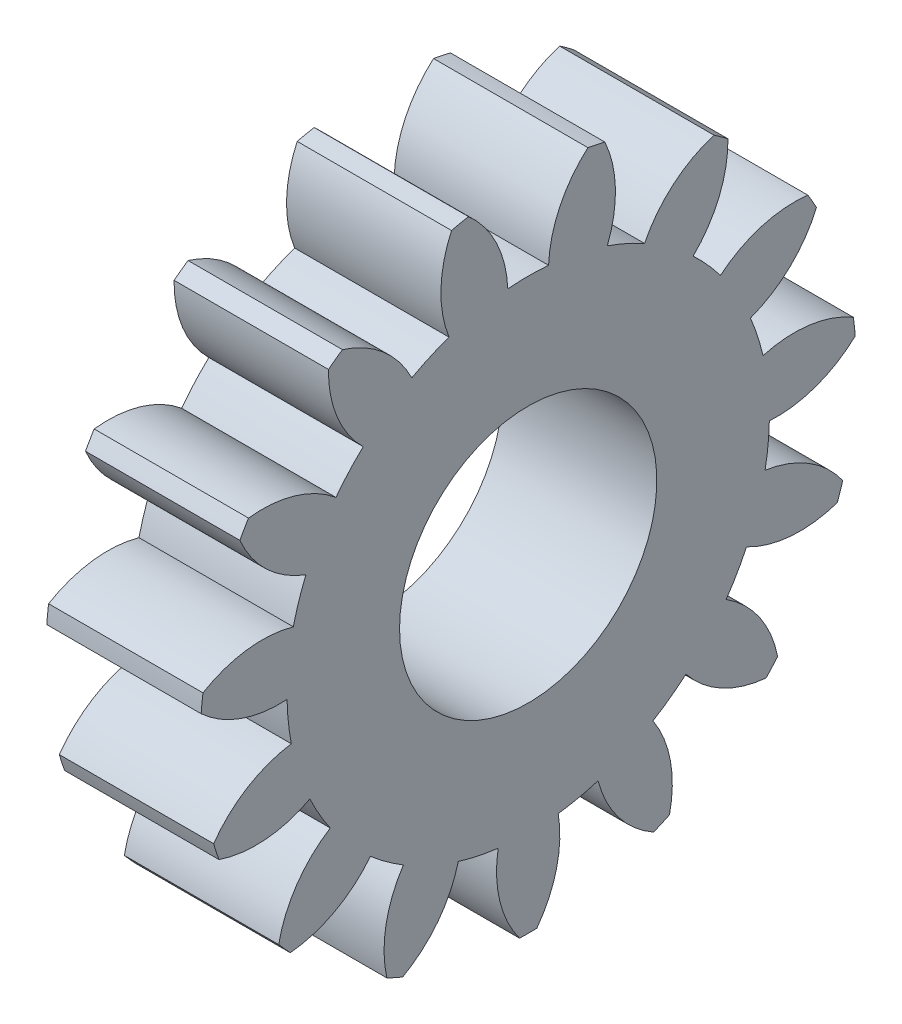
SolidWorks part; units mm, degrees
ref_plane "Plane1" through (0, 0, 0) normal (0, 0, 1) x (1, 0, 0)
ref_plane "Plane2" through (0, 0, 0) normal (0, 1, 0) x (1, 0, 0)
ref_plane "Plane3" through (0, 0, 0) normal (1, 0, 0) x (0, 0, -1)
other "Configuration Table"
sketch "HoldingSke" plane through (0, 0, 0) normal (0, 1, 0) x (1, 0, 0)
  line L0 (0, 0) -> (0.322, -0.0863)
  line L1 (-15, 0) -> (100, 0) construction
  line L2 (0, 0) -> (-2.1039, 2.3779)
  line L3 (0, 0) -> (-11.863, 4.5341)
  line L4 (0, 0) -> (8.3417, 2.2352)
  line L5 (0, 0) -> (-46.8476, -17.4728)
  line L6 (0, 0) -> (-9.9476, -6.7116)
  line L7 (-2.1039, 2.3779) -> (8.6586, 51.2059)
  line L8 (-76.2, 54.61) -> (-73.4, 54.61)
  line L9 (-71.009, 38.7566) -> (-53.1078, 45.2721)
  line L10 (-76.2, 71.12) -> (104.1128, 71.12)
  line L11 (0, 0) -> (-12, 0)
  line L12 (-76.2, 101.6) -> (-76.093, 101.6)
  line L13 (24.9733, 27.94) -> (52.9518, 28.4284)
  line L14 (24.9733, 27.94) -> (24.9743, 27.94)
  line L15 (24.9733, 27.94) -> (100.4006, 29.5858)
  line L16 (-63.627, -3) -> (-12.827, -3)
  circle A0 centre (0, 0) radius 10
  circle A1 centre (0, 0) radius 18.749
  circle A2 centre (0, 0) radius 37.5
  circle A3 centre (0, 0) radius 10
  dimension "MHD" = 37.498
  dimension "Hub_dia" = 75
  dimension "Bore" = 20
  dimension "MBD" = 20
  dimension "Num_teeth" = 15
  dimension "Pitch" = 0.3333
  dimension "Overall_len" = 50
  dimension "Show_teeth" = 15
  dimension "Thickness" = 12
  dimension "OAL" = 50.0001
  dimension "T_dim" = 2.8
  dimension "Ap" = 20
  dimension "H" = 19.05
  dimension "Pitch_radius" = 180.3128
  dimension "Width" = 12
  dimension "Backlash" = 0.107
  dimension "Addendum_fac" = 1
  dimension "Dedendum_fac" = 1.25
  dimension "Clearance_fac" = 0.25
  dimension "Dedendum_add" = 0.001
  dimension "Module" = 3
sketch "BasProSke" plane through (0, 0, 0) normal (0, 1, 0) x (1, 0, 0)
  line L0 (-10, 0) -> (60, 0) construction
  line L1 (0, 0) -> (0, 25.5)
  line L2 (0, 0) -> (12, 0)
  line L3 (12, 0) -> (12, 25.5)
  line L4 (12, 25.5) -> (0, 25.5)
  dimension "Thickness" = 12
  dimension "Diameter" = 51
revolve "Base-Revolve" add sketch "BasProSke" angle 360 about L0
sketch "TooCutSke" plane through (0, 0, 0) normal (1, 0, 0) x (0, 0, -1)
  line L1 (0, 0) -> (0, 107) construction
  line L2 (0, 0) -> (-2.539, 22.3563) construction
  line L3 (0, 0) -> (-9.3126, 43.8125) construction
  line L4 (-2.539, 22.3563) -> (-4.6563, 21.9062) construction
  arc A0 (1.5846, 18.6819) -> (-1.5846, 18.6819) centre (0, 0) ccw
  arc A1 (4.6669, 25.0951) -> (-4.6669, 25.0951) centre (0, 0) ccw
  circle A2 centre (0, 0) radius 22.5 construction
  circle A3 centre (0, 0) radius 21.1431 construction
  arc A4 (-1.5846, 18.6819) -> (-4.6669, 25.0951) centre (-10.5768, 18.3074) ccw
  arc A5 (4.6669, 25.0951) -> (1.5846, 18.6819) centre (10.5768, 18.3074) ccw
  dimension "Root_dia" = 37.498
  dimension "Overcut_dia" = 51.0508
  dimension "Pitch_dia" = 45
  dimension "Base_dia" = 42.2862
  dimension "Flank_rad" = 9
  dimension "Half_ang" = 12
  dimension "Half_CT" = 2.1646
extrude "ToothCut" cut sketch "TooCutSke" along normal through all
fillet "Breaks" [suppressed] radius 0.06
fillet "RootFillets" [suppressed] radius 0.751
pattern_circular "TeethCuts" count 15 every 24 about axis through (-10, 0, 0) along (1, 0, 0) of "ToothCut", "RootFillets", "Breaks"
sketch "HubNeaOneSke" plane through (0, 0, 0) normal (-1, 0, 0) x (0, 0, 1)
  circle A0 centre (0, 0) radius 18.749
  dimension "Diameter" = 37.498
extrude "HubNearOne" [suppressed] add sketch "HubNeaOneSke" along normal blind 38.0001
sketch "HubNeaBotSke" plane through (0, 0, 0) normal (-1, 0, 0) x (0, 0, 1)
  circle A0 centre (0, 0) radius 18.749
  dimension "Diameter" = 37.498
extrude "HubNearBoth" [suppressed] add sketch "HubNeaBotSke" along normal blind 19
ref_plane "FarPln" through (12, 0, 0) normal (1, 0, 0) x (0, 0, -1)
sketch "HubFarSke" plane through (12, 0, 0) normal (1, 0, 0) x (0, 0, -1)
  circle A0 centre (0, 0) radius 18.749
  dimension "Diameter" = 37.498
extrude "HubFar" [suppressed] add sketch "HubFarSke" along normal blind 19
sketch "BorSke" plane through (0, 0, 0) normal (1, 0, 0) x (0, 0, -1)
  circle A0 centre (0, 0) radius 10
  dimension "Diameter" = 20
extrude "Bore" cut sketch "BorSke" along normal mid plane 100.0001
sketch "KeySke" plane through (0, 0, 0) normal (1, 0, 0) x (0, 0, -1)
  line L0 (-3, 0) -> (-3, 12.8)
  line L1 (-3, 12.8) -> (3, 12.8)
  line L2 (3, 12.8) -> (3, 0)
  line L3 (0, 0) -> (0, 34) construction
  line L4 (-3, 0) -> (3, 0)
  dimension "Offset" = 12.8
  dimension "Width" = 6
extrude "Keyway" [suppressed] cut sketch "KeySke" along normal mid plane 100.0001
pattern_circular "Keyway2" [suppressed] count 2 every 90 about axis through (-10, 0, 0) along (1, 0, 0)
equation "' \"Module@HoldingSke\" = 6.35"
equation "' \"Num_teeth@HoldingSke\" = 12"
equation "' \"Ap@HoldingSke\" =  20"
equation "' \"Ap@HoldingSke\" = 20"
equation "' \"Width@HoldingSke\" = 0.5 * 25.4"
equation "' \"Hub_dia@HoldingSke\"= 1 * 25.4"
equation "' \"Hub_dia@HoldingSke\" = 1 * 25.4"
equation "' \"Overall_len@HoldingSke\" = 1.0 * 25.4"
equation "' \"Bore@HoldingSke\" = 0.75 * 25.4"
equation "' \"T_dim@HoldingSke\" = 0.1 * 25.4"
equation "' \"Width@KeySke\" = 0.25 * 25.4"
equation "' \"Show_teeth@HoldingSke\" = 13"
equation "' \"Backlash@HoldingSke\" = 0.009 * 25.4"
equation "' \"Addendum_fac@HoldingSke\" = 1.0"
equation "' \"Dedendum_fac@HoldingSke\" = 1.25"
equation "' \"Dedendum_add@HoldingSke\" = 0.00005 * 25.4"
equation "' \"Clearance_fac@HoldingSke\" = 0.25"
equation "\"Pitch@HoldingSke\" = 1 / \"Module@HoldingSke\""
equation "\"Overcut_dia@TooCutSke\" = (\"Num_teeth@HoldingSke\" + 2 * \"Addendum_fac@HoldingSke\") / \"Pitch@HoldingSke\" + 0.002 * 25.4"
equation "\"Pitch_dia@TooCutSke\" = \"Num_teeth@HoldingSke\" / \"Pitch@HoldingSke\""
equation "\"Base_dia@TooCutSke\" = \"Num_teeth@HoldingSke\" / \"Pitch@HoldingSke\" * cos((\"Ap@HoldingSke\"  * 3.14159265 / 180))"
equation "\"Root_dia@TooCutSke\" = (\"Num_teeth@HoldingSke\" + 2) / \"Pitch@HoldingSke\" - 2 * (\"Addendum_fac@HoldingSke\" + \"Dedendum_fac@HoldingSke\") / \"Pitch@HoldingSke\" - \"Dedendum_add@HoldingSke\" * 2"
equation "\"Half_ang@TooCutSke\" = 180 / \"Num_teeth@HoldingSke\""
equation "\"Half_CT@TooCutSke\" = \"Num_teeth@HoldingSke\" / \"Pitch@HoldingSke\" * sin((3.14159265 / 2 / \"Num_teeth@HoldingSke\")) / 2 - 7 * \"Backlash@HoldingSke\" / 4"
equation "\"Flank_rad@TooCutSke\" = \"Num_teeth@HoldingSke\" / \"Pitch@HoldingSke\" / 5"
equation "\"Radius@RootFillets\" = \"Clearance_fac@HoldingSke\" / \"Pitch@HoldingSke\" + \"Dedendum_add@HoldingSke\""
equation "\"Break_rad@Breaks\" = 0.02 / \"Pitch@HoldingSke\""
equation "\"Thickness@HoldingSke\" = \"Width@HoldingSke\""
equation "\"OAL@HoldingSke\" = \"Thickness@HoldingSke\""
equation "\"MHD@HoldingSke\" = (\"Num_teeth@HoldingSke\" + 2) / \"Pitch@HoldingSke\" - 2 * (\"Addendum_fac@HoldingSke\" + \"Dedendum_fac@HoldingSke\")  / \"Pitch@HoldingSke\" - \"Dedendum_add@HoldingSke\" * 2"
equation "\"MBD@HoldingSke\" = (\"Num_teeth@HoldingSke\" + 2) / \"Pitch@HoldingSke\" - 2 * (\"Addendum_fac@HoldingSke\" + \"Dedendum_fac@HoldingSke\")  / \"Pitch@HoldingSke\" - \"Dedendum_add@HoldingSke\" * 2 - 0.002 * 25.4"
equation "\"MHD@HoldingSke\" = ((sgn( \"MHD@HoldingSke\" - \"Hub_dia@HoldingSke\" )-1)*( \"MHD@HoldingSke\" - \"Hub_dia@HoldingSke\" ))/-2+ \"Hub_dia@HoldingSke\""
equation "\"MBD@HoldingSke\" = ((sgn( \"MBD@HoldingSke\" - \"Bore@HoldingSke\" )-1)*( \"MBD@HoldingSke\" - \"Bore@HoldingSke\" ))/-2+ \"Bore@HoldingSke\""
equation "\"OAL@HoldingSke\" = ((sgn( \"OAL@HoldingSke\" - \"Overall_len@HoldingSke\" )+1)*( \"OAL@HoldingSke\" - \"Overall_len@HoldingSke\" ))/2 + \"Overall_len@HoldingSke\" + 0.000002 * 25.4"
equation "\"Num_teeth@TeethCuts\" = int( \"Show_teeth@HoldingSke\" ) + 1"
equation "\"Num_teeth@TeethCuts\" = ((sgn( \"Num_teeth@TeethCuts\" - \"Num_teeth@HoldingSke\" )-1)*( \"Num_teeth@TeethCuts\" - \"Num_teeth@HoldingSke\" ))/-2+ \"Num_teeth@HoldingSke\""
equation "\"Num_teeth@TeethCuts\" = ((sgn( \"Num_teeth@TeethCuts\" - 2.0)+1)*( \"Num_teeth@TeethCuts\" - 2.0))/2 +2.0"
equation "\"Angle@TeethCuts\" = 360.0 / \"Num_teeth@HoldingSke\""
equation "\"Diameter@BasProSke\" = (\"Num_teeth@HoldingSke\" + 2 * \"Addendum_fac@HoldingSke\") / \"Pitch@HoldingSke\""
equation "\"Thickness@BasProSke\"  = \"Thickness@HoldingSke\""
equation "' \"Fillet_rad@BasProSke\" =  \"Thickness@HoldingSke\" * 0.05"
equation "' \"Fillet_rad@BasProSke\" = \"Thickness@HoldingSke\" * 0.05"
equation "\"MHD@HoldingSke\" = ((sgn( \"MHD@HoldingSke\" - \"Root_dia@TooCutSke\" )-1)*( \"MHD@HoldingSke\" - \"Root_dia@TooCutSke\" ))/-2+ \"Root_dia@TooCutSke\""
equation "\"Diameter@HubNeaOneSke\" = \"MHD@HoldingSke\""
equation "\"Length@HubNearOne\" = \"OAL@HoldingSke\" - \"Thickness@BasProSke\""
equation "\"Diameter@HubNeaBotSke\" = \"MHD@HoldingSke\""
equation "\"Length@HubNearBoth\" = ( \"OAL@HoldingSke\" - \"Thickness@BasProSke\" ) / 2.0"
equation "\"Thickness@FarPln\" = \"Thickness@BasProSke\""
equation "\"Diameter@HubFarSke\" = \"MHD@HoldingSke\""
equation "\"Length@HubFar\" = ( \"OAL@HoldingSke\" - \"Thickness@BasProSke\" ) / 2.0"
equation "\"Diameter@BorSke\" = \"MBD@HoldingSke\""
equation "\"D1@Bore\" = \"OAL@HoldingSke\" * 2.0"
equation "\"D1@Keyway\" = \"OAL@HoldingSke\" * 2.0"
equation "\"Offset@KeySke\" = \"T_dim@HoldingSke\" + \"MBD@HoldingSke\" / 2.0"
